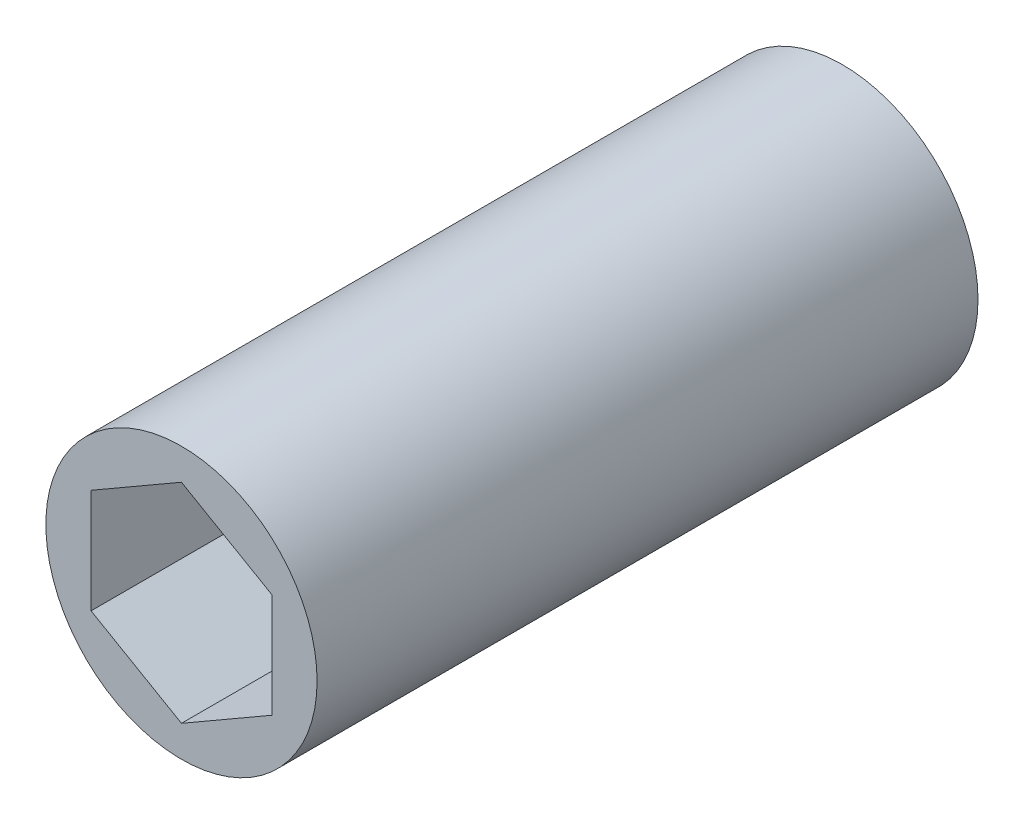
SolidWorks part; units mm, degrees
material "PET"
ref_plane "Front Plane" through (0, 0, 0) normal (0, 0, 1) x (1, 0, 0)
ref_plane "Top Plane" through (0, 0, 0) normal (0, 1, 0) x (1, 0, 0)
ref_plane "Right Plane" through (0, 0, 0) normal (1, 0, 0) x (0, 0, -1)
sketch "Sketch1" plane through (0, 0, 0) normal (0, 0, 1) x (1, 0, 0)
  line L1 (0, 7.3323) -> (-6.35, 3.6662)
  line L2 (-6.35, 3.6662) -> (-6.35, -3.6662)
  line L3 (-6.35, -3.6662) -> (0, -7.3323)
  line L4 (0, -7.3323) -> (6.35, -3.6662)
  line L5 (6.35, -3.6662) -> (6.35, 3.6662)
  line L6 (6.35, 3.6662) -> (0, 7.3323)
  circle A0 centre (0, 0) radius 9.525
  circle A1 centre (0, 0) radius 6.35 construction
  point P3 (0, 0)
  dimension "D1" = 19.05
  dimension "D2" = 12.7
extrude "Boss-Extrude1" add sketch "Sketch1" along normal mid plane 46.4185
